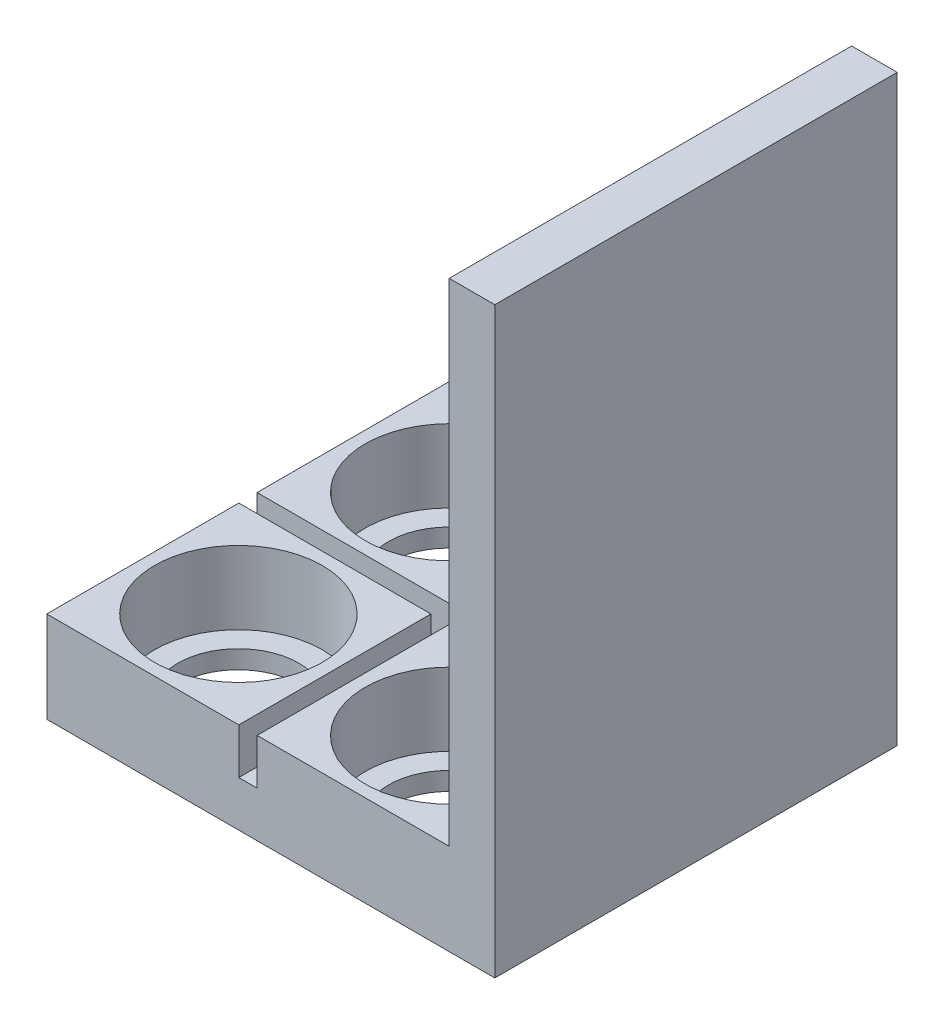
SolidWorks part; units mm, degrees
material "Melamine resin"
ref_plane "Front Plane" through (0, 0, 0) normal (0, 0, 1) x (1, 0, 0)
ref_plane "Top Plane" through (0, 0, 0) normal (0, 1, 0) x (1, 0, 0)
ref_plane "Right Plane" through (0, 0, 0) normal (1, 0, 0) x (0, 0, -1)
sketch "Sketch1" plane through (0, 0, 0) normal (0, 1, 0) x (1, 0, 0)
  line L1 (0, 22.05) -> (44.1, 22.05)
  line L2 (0, 22.05) -> (0, -22.05)
  line L3 (0, -22.05) -> (44.1, -22.05)
  line L4 (44.1, 22.05) -> (44.1, -22.05)
  point P4 (0, 0)
  dimension "D1" = 44.1
  dimension "D2" = 44.1
extrude "Boss-Extrude1" add sketch "Sketch1" along normal blind 10
sketch "Sketch2" plane through (0, 10, 0) normal (0, 1, 0) x (1, 0, 0)
  line L0 (44.1, 22.05) -> (0, 22.05) construction
  line L2 (22.05, 22.05) -> (22.05, -22.05) construction
  line L3 (0, -22.05) -> (44.1, -22.05) construction
  line L4 (22.05, 22.05) -> (0, 22.05)
  line L6 (0, 22.05) -> (0, -22.05) construction
  circle A0 centre (10.5, 11.55) radius 9.2
  dimension "D1" = 18.4
  dimension "D2" = 10.5
  dimension "D3" = 10.5
extrude "Cut-Extrude1" cut sketch "Sketch2" against normal blind 8 contours A0
sketch "Sketch5" plane through (0, 2, 0) normal (0, 1, 0) x (1, 0, 0)
  circle A0 centre (10.5, 11.55) radius 6.65
  dimension "D1" = 13.3
extrude "Cut-Extrude4" cut sketch "Sketch5" against normal through all
mirror "Mirror1" about plane through (0, 0, 0) normal (0, 0, 1) of "Cut-Extrude4", "Cut-Extrude1"
ref_plane "Plane2" through (22.05, 0, 0) normal (1, 0, 0) x (0, 0, -1)
mirror "Mirror2" about plane through (22.05, 0, 0) normal (1, 0, 0) of "Cut-Extrude1", "Mirror1", "Cut-Extrude4"
sketch "Sketch4" plane through (0, 10, 0) normal (0, 1, 0) x (1, 0, 0)
  line L0 (44.1, 22.05) -> (0, 22.05) construction
  line L1 (21.05, 22.05) -> (23.05, 22.05)
  line L2 (21.05, 22.05) -> (21.05, 1)
  line L3 (21.05, -23.3627) -> (23.05, -23.3627)
  line L4 (23.05, 22.05) -> (23.05, 1)
  line L5 (22.05, -5.5) -> (22.05, 5.5) construction
  line L6 (23.05, -1) -> (23.05, -23.3627)
  line L11 (0, 1) -> (21.05, 1)
  line L12 (0, 1) -> (0, -1)
  line L13 (0, -1) -> (21.05, -1)
  line L14 (46.2514, 1) -> (46.2514, -1)
  line L15 (21.05, -1) -> (21.05, -23.3627)
  line L16 (23.05, 1) -> (46.2514, 1)
  line L17 (23.05, -1) -> (46.2514, -1)
  point P6 (22.05, 22.05)
  point P13 (0, 0)
  dimension "D1" = 2
  dimension "D2" = 2
extrude "Cut-Extrude3" cut sketch "Sketch4" against normal blind 5
sketch "Sketch6" plane through (44.1, 0, 0) normal (1, 0, 0) x (0, 0, -1)
  line L1 (-22.05, 10) -> (22.05, 10)
  line L2 (-22.05, 10) -> (-22.05, 0)
  line L3 (-22.05, 0) -> (22.05, 0)
  line L4 (22.05, 10) -> (22.05, 0)
extrude "Boss-Extrude2" add sketch "Sketch6" along normal blind 5
sketch "Sketch7" plane through (0, 10, 0) normal (0, 1, 0) x (1, 0, 0)
  line L0 (23.05, -22.05) -> (49.1, -22.05) construction
  line L1 (49.1, 22.05) -> (44.1, 22.05)
  line L2 (49.1, 22.05) -> (49.1, -22.05)
  line L3 (49.1, -22.05) -> (44.1, -22.05)
  line L4 (44.1, 22.05) -> (44.1, -22.05)
  dimension "D1" = 5
extrude "Boss-Extrude3" add sketch "Sketch7" along normal blind 53.9
